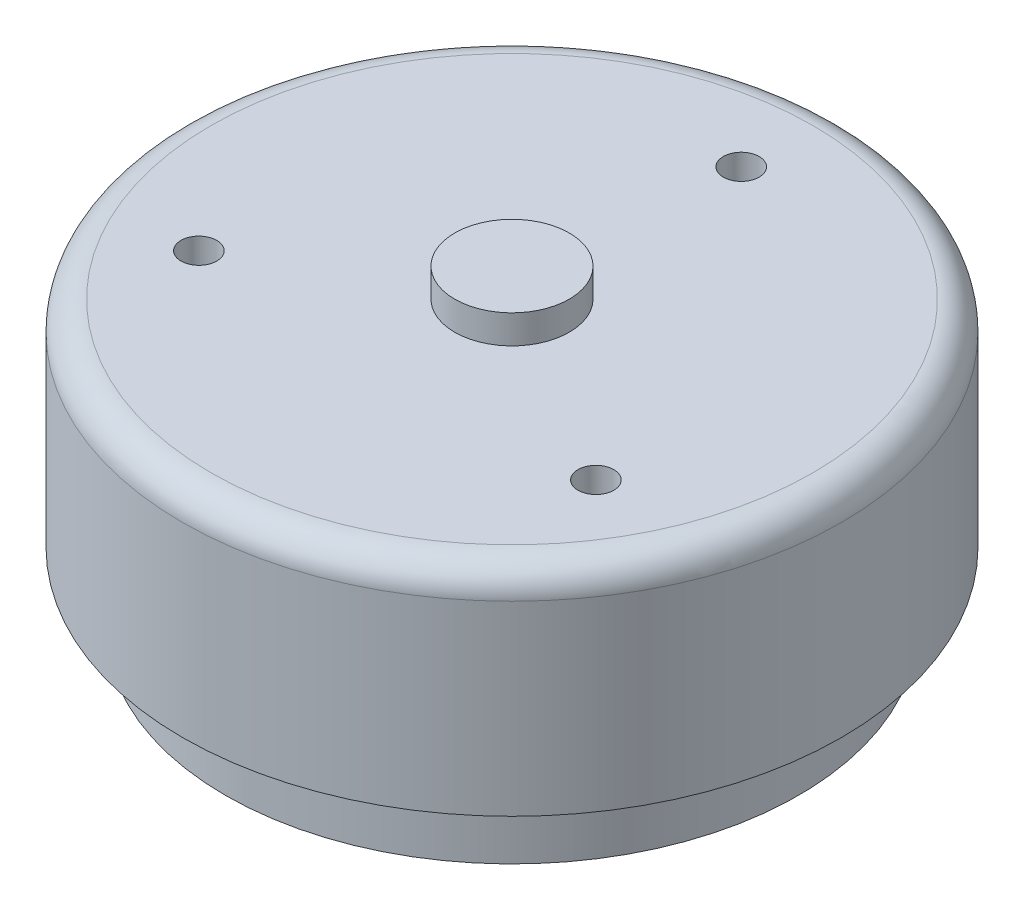
SolidWorks part; units mm, degrees
material "1060-H18"
ref_plane "Front Plane" through (0, 0, 0) normal (0, 0, 1) x (1, 0, 0)
ref_plane "Top Plane" through (0, 0, 0) normal (0, 1, 0) x (1, 0, 0)
ref_plane "Right Plane" through (0, 0, 0) normal (1, 0, 0) x (0, 0, -1)
sketch "Sketch6" plane through (0, 0, 0) normal (0, 1, 0) x (1, 0, 0)
  circle A0 centre (0, 0) radius 23
  dimension "D1" = 46
extrude "Boss-Extrude3" add sketch "Sketch6" along normal blind 25
sketch "Sketch7" plane through (0, 0, 0) normal (0, 1, 0) x (1, 0, 0)
  line L0 (0, 0) -> (-6, 0) construction
  line L1 (0, 0) -> (0, 6) construction
  circle A0 centre (-6, 0) radius 1.5
  circle A1 centre (0, 6) radius 1.5
  circle A2 centre (6, 0) radius 1.5
  circle A3 centre (0, -6) radius 1.5
  dimension "D1" = 90
extrude "Cut-Extrude2" cut sketch "Sketch7" along normal blind 5
sketch "Sketch8" plane through (0, 25, 0) normal (0, 1, 0) x (1, 0, 0)
  line L0 (0, 0) -> (-13.8564, -8) construction
  line L1 (0, 0) -> (0, 16) construction
  circle A0 centre (-13.8564, -8) radius 1.25
  circle A1 centre (0, 16) radius 1.25
  circle A2 centre (13.8564, -8) radius 1.25
  dimension "D1" = 120
extrude "Cut-Extrude3" cut sketch "Sketch8" against normal blind 5
sketch "Sketch9" plane through (0, 25, 0) normal (0, 1, 0) x (1, 0, 0)
  circle A0 centre (0, 0) radius 4
extrude "Boss-Extrude4" add sketch "Sketch9" along normal blind 2
sketch "Sketch10" plane through (0, 0, 0) normal (0, -1, 0) x (1, 0, 0)
  circle A0 centre (0, 0) radius 2
extrude "Boss-Extrude5" add sketch "Sketch10" along normal blind 3
fillet "Fillet1" radius 5 1 edges at (0, 0, 23)
fillet "Fillet2" radius 2 1 edges at (0, 25, 23)
sketch "Sketch11" plane through (0, 0, 0) normal (1, 0, 0) x (0, 0, -1)
  line L0 (55, 0) -> (-55, 0) construction
  line L1 (-26.5606, 10) -> (36.5792, 10)
  line L2 (-26.5606, 10) -> (-26.5606, -14.1578)
  line L3 (-26.5606, -14.1578) -> (36.5792, -14.1578)
  line L4 (36.5792, 10) -> (36.5792, -14.1578)
  dimension "D1" = 10
extrude "Cut-Extrude4" cut sketch "Sketch11" against normal mid plane 100
sketch "Sketch12" plane through (0, 10, 0) normal (0, -1, 0) x (1, 0, 0)
  circle A0 centre (0, 0) radius 20
extrude "Boss-Extrude6" add sketch "Sketch12" along normal blind 5
